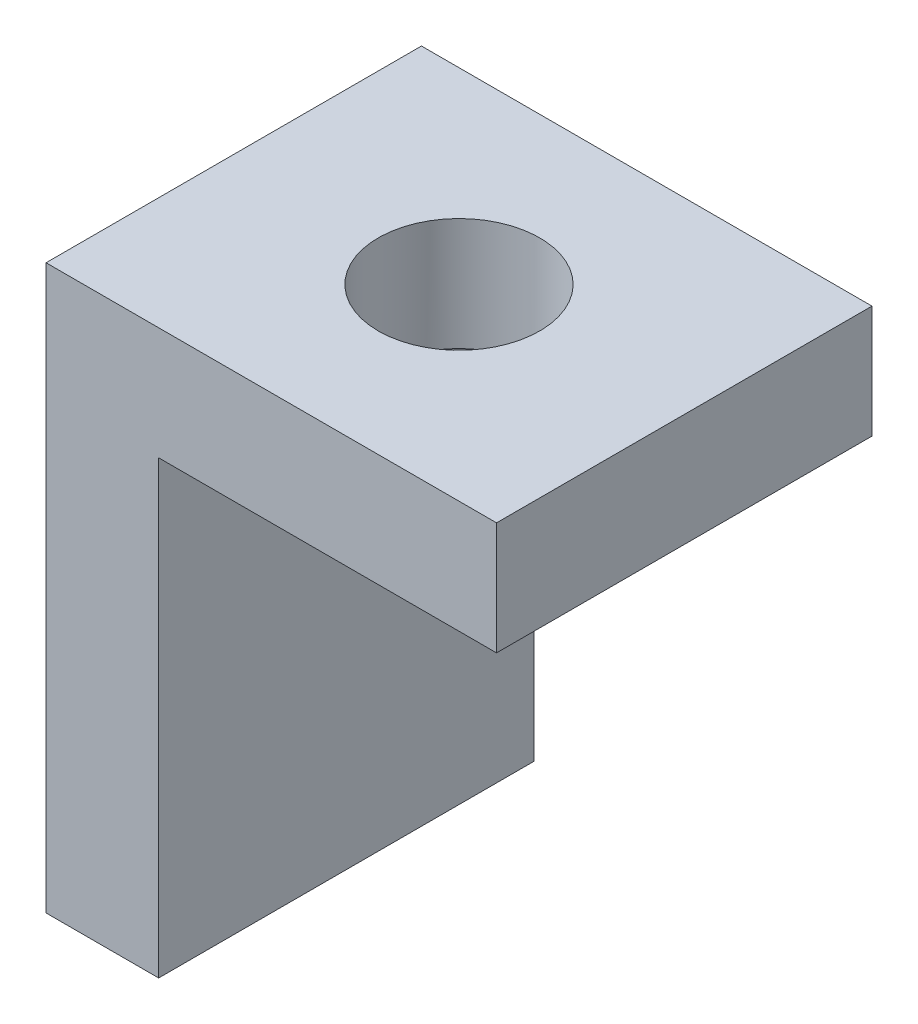
SolidWorks part; units mm, degrees
material "PVC"
ref_plane "Front" through (0, 0, 0) normal (0, 0, 1) x (1, 0, 0)
ref_plane "Top" through (0, 0, 0) normal (0, 1, 0) x (1, 0, 0)
ref_plane "Right" through (0, 0, 0) normal (1, 0, 0) x (0, 0, -1)
sketch "Esquisse1" plane through (0, 0, 0) normal (0, 0, 1) x (1, 0, 0)
  line L0 (-9, 0) -> (-12, 0)
  line L1 (-12, 0) -> (-12, 15)
  line L2 (-12, 15) -> (0, 15)
  line L3 (0, 15) -> (0, 12)
  line L4 (0, 12) -> (-9, 12)
  line L5 (-9, 12) -> (-9, 0)
  dimension "D1" = 3
  dimension "D2" = 9
  dimension "D3" = 12
extrude "Boss.-Extru.1" add sketch "Esquisse1" along normal blind 10
hole_wizard "Dégagement M41" positions "Esquisse2" profile "Esquisse3" hole size "M4" standard "ISO" end condition through all
sketch "Esquisse2" plane through (0, 15, 0) normal (0, 1, 0) x (1, 0, 0)
  line L1 (-9, -10) -> (-9, 0) construction
  line L2 (0, -5) -> (-9, -5) construction
  line L3 (0, -10) -> (0, 0) construction
  point P0 (-6, -5)
  dimension "D1" = 3
sketch "Esquisse3" plane through (-6, 15, 5) normal (1, 0, 0) x (0, 0, 1)
  line L0 (0, 0) -> (0, 15)
  line L1 (0, 15) -> (2.15, 15)
  line L2 (2.15, 15) -> (2.15, 0)
  line L5 (2.15, 0) -> (0, 0)
  line L11 (0, -6.35) -> (0, 107.95) construction
  dimension "Diamètre du perçage jusqu'au prochain" = 4.3
  dimension "Profondeur du perçage jusqu'au prochain" = 15
